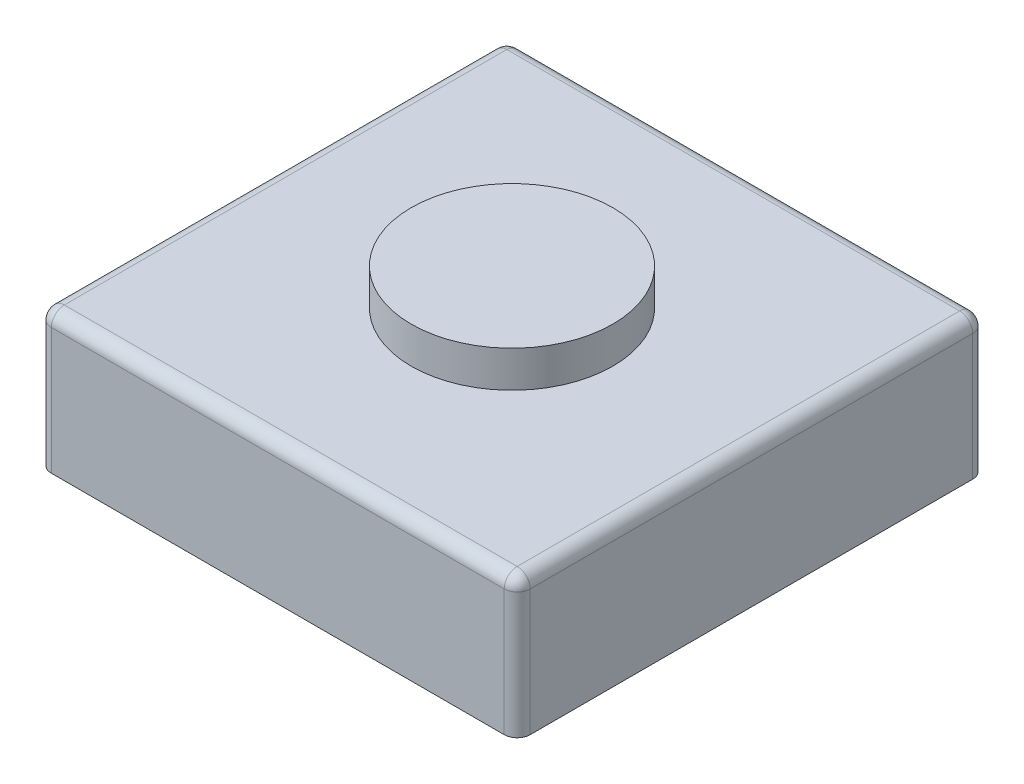
SolidWorks part; units mm, degrees
material "商用纯 CP-Ti UNS R50400 (SS)"
ref_plane "前视基准面" through (0, 0, 0) normal (0, 0, 1) x (1, 0, 0)
ref_plane "上视基准面" through (0, 0, 0) normal (0, 1, 0) x (1, 0, 0)
ref_plane "右视基准面" through (0, 0, 0) normal (1, 0, 0) x (0, 0, -1)
other "Configuration Table"
sketch "草图1" plane through (0, 0, 0) normal (0, 1, 0) x (1, 0, 0)
  line L1 (-15.9344, 10.3279) -> (20.8656, 10.3279)
  line L2 (-15.9344, 10.3279) -> (-15.9344, -25.6721)
  line L3 (-15.9344, -25.6721) -> (20.8656, -25.6721)
  line L4 (20.8656, 10.3279) -> (20.8656, -25.6721)
  dimension "D1" = 36.8
  dimension "D2" = 36
extrude "凸台-拉伸1" add sketch "草图1" along normal blind 10.7
fillet "圆角1" radius 1 8 edges at (2.4656, 10.7, -10.3279) (20.8656, 10.7, 7.6721) (2.4656, 10.7, 25.6721) (-15.9344, 10.7, 7.6721) (-15.9344, 5.35, 25.6721) (-15.9344, 5.35, -10.3279) (20.8656, 5.35, -10.3279) (20.8656, 5.35, 25.6721)
sketch "草图2" plane through (0, 10.7, 0) normal (0, 1, 0) x (1, 0, 0)
  line L0 (-14.9344, -7.6721) -> (19.8656, -7.6721) construction
  line L1 (-14.9344, 9.3279) -> (-14.9344, -24.6721) construction
  line L2 (19.8656, -24.6721) -> (19.8656, 9.3279) construction
  line L3 (2.4656, 9.3279) -> (2.4656, -24.6721) construction
  line L4 (19.8656, 9.3279) -> (-14.9344, 9.3279) construction
  line L5 (-14.9344, -24.6721) -> (19.8656, -24.6721) construction
  circle A0 centre (2.4656, -7.6721) radius 7.75
  dimension "D1" = 15.5
extrude "凸台-拉伸2" add sketch "草图2" along normal blind 2.8
